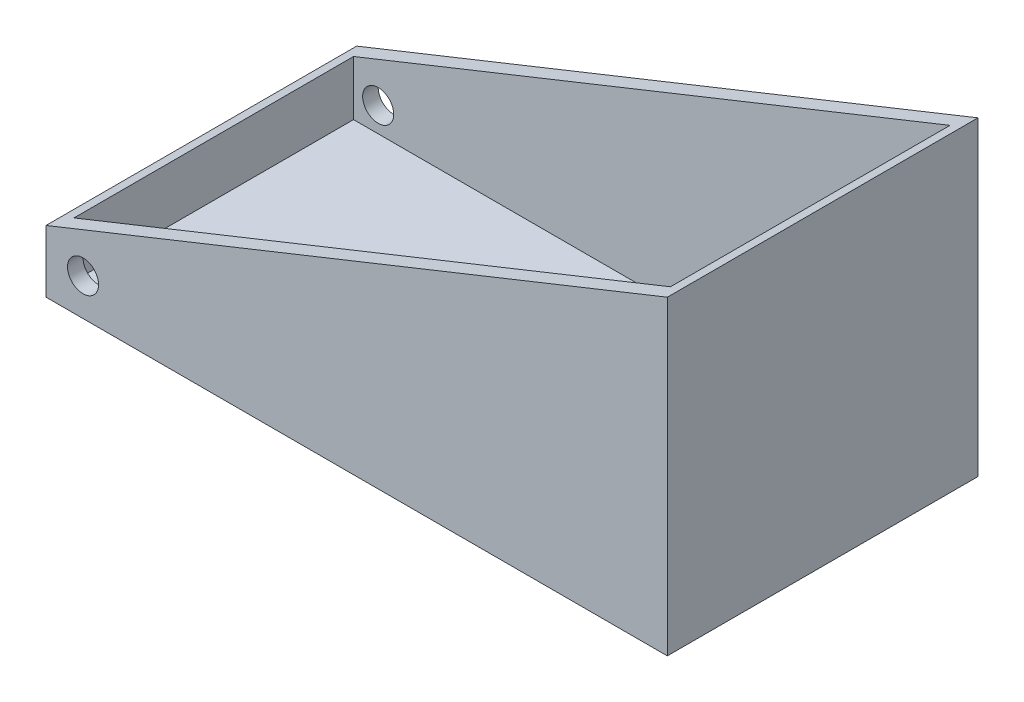
SolidWorks part; units mm, degrees
ref_plane "Front Plane" through (0, 0, 0) normal (0, 0, 1) x (1, 0, 0)
ref_plane "Top Plane" through (0, 0, 0) normal (0, 1, 0) x (1, 0, 0)
ref_plane "Right Plane" through (0, 0, 0) normal (1, 0, 0) x (0, 0, -1)
sketch "Sketch1" plane through (0, 0, 0) normal (0, 0, 1) x (1, 0, 0)
  line L0 (0, 0.251) -> (0, 7.5869)
  line L1 (0, 7.5869) -> (100, 47.5869)
  line L2 (100, 47.5869) -> (100, -2.4131)
  line L3 (100, -2.4131) -> (0, -2.4131)
  line L4 (0, -2.4131) -> (0, 0.251)
  dimension "D1" = 10
  dimension "D2" = 50
  dimension "D3" = 100
extrude "Boss-Extrude1" add sketch "Sketch1" along normal blind 50
sketch "Sketch3" plane through (0, -2.4131, 0) normal (0, -1, 0) x (1, 0, 0)
  line L0 (0, 50) -> (100, 50) construction
  line L5 (4, 47.5) -> (96, 2.5) construction
  line L6 (4, 2.5) -> (96, 47.5) construction
  line L7 (0, 0) -> (100, 0) construction
  line L8 (2, 47.5) -> (2, 2.5)
  line L9 (2, 47.5) -> (98, 47.5)
  line L10 (98, 47.5) -> (98, 2.5)
  line L11 (2, 2.5) -> (98, 2.5)
  point P4 (50, 25)
  dimension "D1" = 2.5
  dimension "D2" = 2.5
extrude "Cut-Extrude9" cut sketch "Sketch3" against normal through all from offset 2 offset against normal yes
sketch "Sketch4" plane through (0, 0, 0) normal (0, 0, -1) x (-1, 0, 0)
  circle A1 centre (-5.9629, 3.5498) radius 2.5
extrude "Cut-Extrude10" cut sketch "Sketch4" against normal through all
